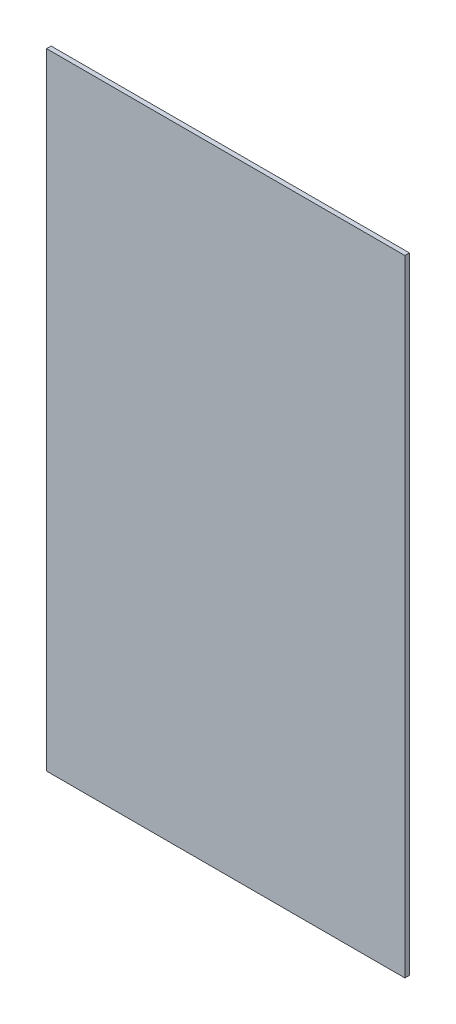
SolidWorks part; units mm, degrees
ref_plane "Front Plane" through (0, 0, 0) normal (0, 0, 1) x (1, 0, 0)
ref_plane "Top Plane" through (0, 0, 0) normal (0, 1, 0) x (1, 0, 0)
ref_plane "Right Plane" through (0, 0, 0) normal (1, 0, 0) x (0, 0, -1)
sketch "Sketch1" plane through (0, 0, 0) normal (0, 0, 1) x (1, 0, 0)
  line L1 (-30.5262, 77.2604) -> (32.4738, 77.2604)
  line L2 (-30.5262, 77.2604) -> (-30.5262, -32.7396)
  line L3 (-30.5262, -32.7396) -> (32.4738, -32.7396)
  line L4 (32.4738, 77.2604) -> (32.4738, -32.7396)
  dimension "D1" = 110
  dimension "D2" = 63
extrude "Boss-Extrude1" add sketch "Sketch1" along normal blind 0.8
